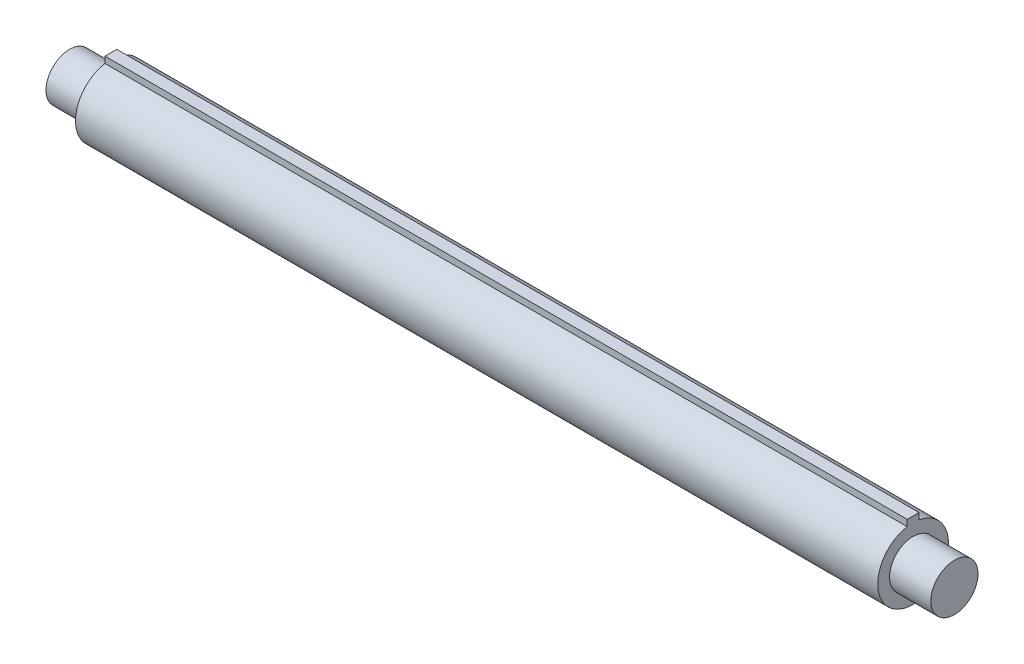
SolidWorks part; units mm, degrees
ref_plane "Front Plane" through (0, 0, 0) normal (0, 0, 1) x (1, 0, 0)
ref_plane "Top Plane" through (0, 0, 0) normal (0, 1, 0) x (1, 0, 0)
ref_plane "Right Plane" through (0, 0, 0) normal (1, 0, 0) x (0, 0, -1)
sketch "Sketch1" plane through (0, 0, 0) normal (0, 0, 1) x (1, 0, 0)
  line L0 (0, 0) -> (-75, 0)
  line L1 (-75, 0) -> (-75, 2)
  line L2 (-75, 2) -> (-71.5, 2)
  line L3 (-71.5, 2) -> (-71.5, 3)
  line L4 (-71.5, 3) -> (-3.5, 3)
  line L5 (-3.5, 3) -> (-3.5, 2)
  line L6 (-3.5, 2) -> (0, 2)
  line L7 (0, 2) -> (0, 0)
  dimension "D1" = 3.5
  dimension "D2" = 68
  dimension "D3" = 2
  dimension "D4" = 3
revolve "Revolve1" add sketch "Sketch1" angle 360 about L0
sketch "Sketch2" plane through (-71.5, 0, 0) normal (-1, 0, 0) x (0, 0, 1)
  line L1 (-0.5, 2.5) -> (0.5, 2.5)
  line L2 (-0.5, 2.5) -> (-0.5, 3.5)
  line L3 (-0.5, 3.5) -> (0.5, 3.5)
  line L4 (0.5, 2.5) -> (0.5, 3.5)
  line L5 (-0.5, 2.5) -> (0.5, 3.5) construction
  line L6 (-0.5, 3.5) -> (0.5, 2.5) construction
  circle A0 centre (0, 0) radius 3 construction
  point P0 (0, 3)
  dimension "D1" = 1
  dimension "D2" = 1
extrude "Boss-Extrude1" add sketch "Sketch2" against normal up to surface (68 mm away) up to face at (-3.5, 3, 0)
